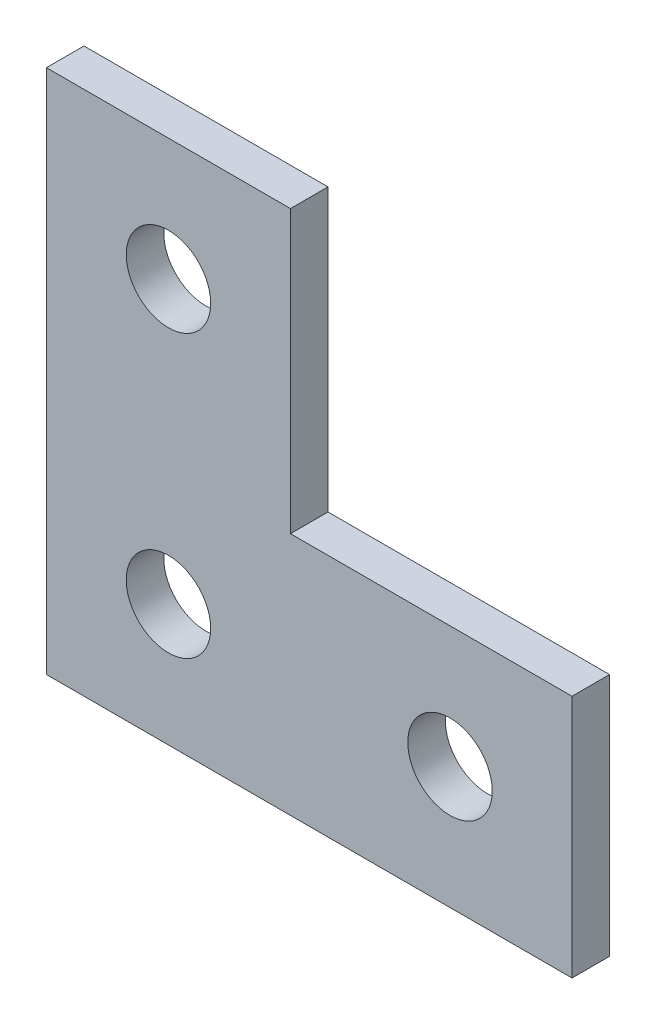
SolidWorks part; units mm, degrees
ref_plane "Front Plane" through (0, 0, 0) normal (0, 0, 1) x (1, 0, 0)
ref_plane "Top Plane" through (0, 0, 0) normal (0, 1, 0) x (1, 0, 0)
ref_plane "Right Plane" through (0, 0, 0) normal (1, 0, 0) x (0, 0, -1)
sketch "Sketch1" plane through (0, 0, 0) normal (0, 0, 1) x (1, 0, 0)
  line L0 (0, 88.9) -> (0, 0)
  line L1 (0, 0) -> (88.9, 0)
  line L2 (88.9, 0) -> (88.9, 41.275)
  line L3 (88.9, 41.275) -> (41.275, 41.275)
  line L4 (41.275, 41.275) -> (41.275, 88.9)
  line L5 (41.275, 88.9) -> (0, 88.9)
  line L6 (20.6375, 88.9) -> (20.6375, 20.6375) construction
  line L7 (20.6375, 20.6375) -> (88.9, 20.6375) construction
  circle A0 centre (20.6375, 20.6375) radius 7.1438
  circle A1 centre (20.6375, 68.2625) radius 7.1438
  circle A2 centre (68.2625, 20.6375) radius 7.1438
  dimension "Hole Size" = 14.2875
  dimension "D1" = 41.275
  dimension "A" = 88.9
  dimension "Spacing" = 47.625
  dimension "D5" = 47.625
extrude "Boss-Extrude1" add sketch "Sketch1" along normal mid plane 6.35
equation "\"D5@Sketch1\" = \"Spacing@Sketch1\""
